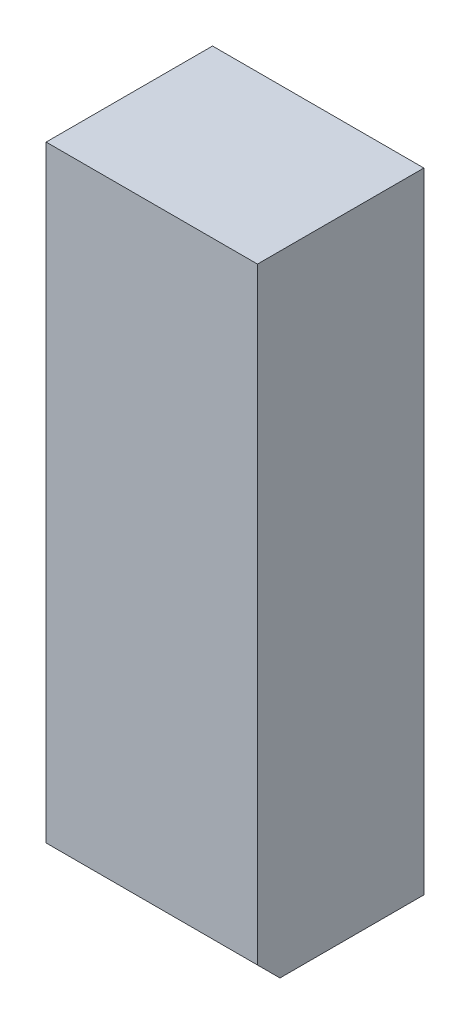
SolidWorks part; units mm, degrees
material "Material"
ref_plane "Front Plane" through (0, 0, 0) normal (0, 0, 1) x (1, 0, 0)
ref_plane "Top Plane" through (0, 0, 0) normal (0, 1, 0) x (1, 0, 0)
ref_plane "Right Plane" through (0, 0, 0) normal (1, 0, 0) x (0, 0, -1)
ref_plane "Plane1" through (0, 0, 0) normal (-1, 0, 0) x (0, -1, 0)
sketch "Sketch1" plane through (0, 0, 0) normal (-1, 0, 0) x (0, -1, 0)
  line L0 (140, 0) -> (140, 32)
  line L1 (140, 32) -> (135, 37)
  line L2 (135, 37) -> (0, 37)
  line L3 (0, 37) -> (0, 0)
  line L4 (0, 0) -> (140, 0)
extrude "Boss-Extrude1" add sketch "Sketch1" against normal blind 47
